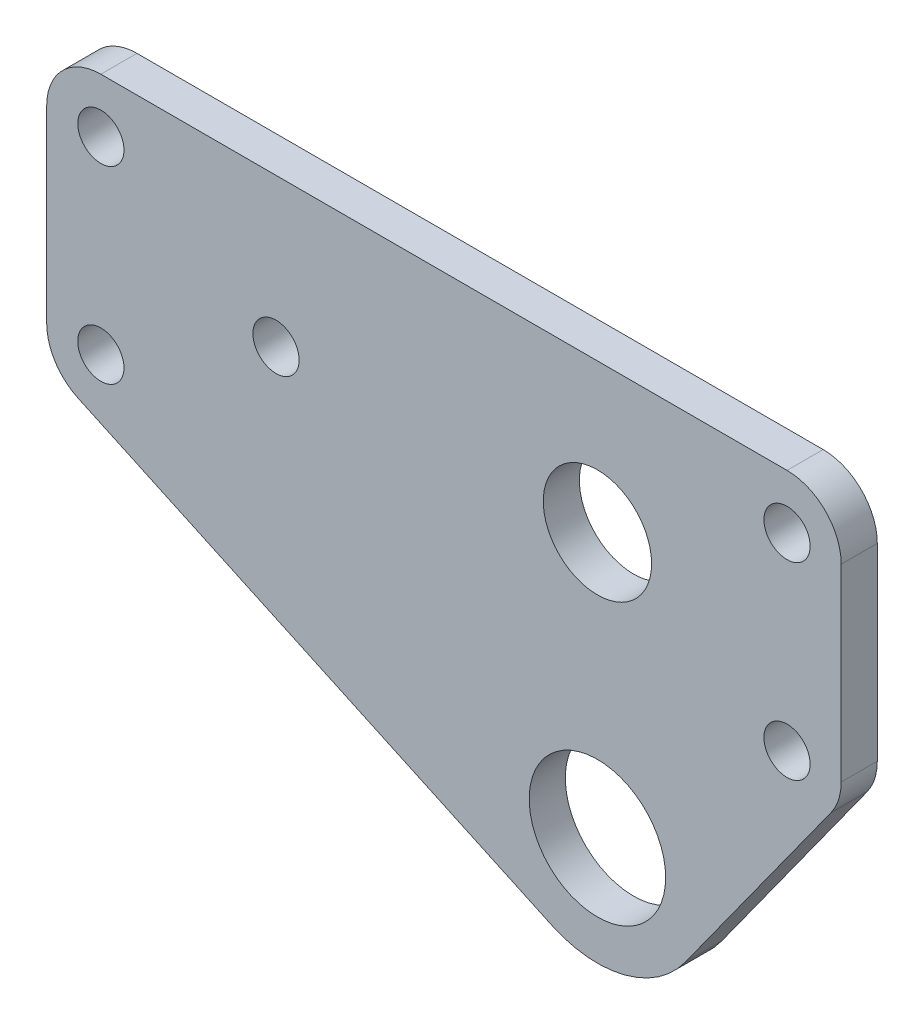
SolidWorks part; units mm, degrees
ref_plane "Front Plane" through (0, 0, 0) normal (0, 0, 1) x (1, 0, 0)
ref_plane "Top Plane" through (0, 0, 0) normal (0, 1, 0) x (1, 0, 0)
ref_plane "Right Plane" through (0, 0, 0) normal (1, 0, 0) x (0, 0, -1)
sketch "Sketch1" plane through (0, 0, 0) normal (0, 0, 1) x (1, 0, 0)
  line L0 (0, 0) -> (26.9875, 0) construction
  line L2 (43.6562, -13.0556) -> (-16.6687, -13.0556)
  line L3 (48.4188, -8.2931) -> (48.4188, 8.2931)
  line L4 (43.6562, 13.0556) -> (-16.6687, 13.0556)
  line L5 (-21.4312, -8.2931) -> (-21.4312, 8.2931)
  line L6 (48.4188, -13.0556) -> (-21.4312, 13.0556) construction
  line L7 (48.4188, 13.0556) -> (-21.4312, -13.0556) construction
  circle A0 centre (0, 0) radius 6 construction
  circle A1 centre (26.9875, 0) radius 4.7625
  arc A2 (48.4188, 8.2931) -> (43.6562, 13.0556) centre (43.6562, 8.2931) ccw
  arc A3 (43.6562, -13.0556) -> (48.4188, -8.2931) centre (43.6562, -8.2931) ccw
  arc A4 (-16.6687, -13.0556) -> (-21.4312, -8.2931) centre (-16.6687, -8.2931) cw
  arc A5 (-16.6687, 13.0556) -> (-21.4312, 8.2931) centre (-16.6687, 8.2931) ccw
  circle A6 centre (0, 0) radius 13.7592 construction
  circle A7 centre (26.9875, 0) radius 15.3467 construction
  circle A8 centre (-16.6687, 8.2931) radius 2.032
  circle A9 centre (43.6562, 8.2931) radius 2.032
  circle A10 centre (-16.6687, -8.2931) radius 2.032
  circle A11 centre (43.6562, -8.2931) radius 2.032
  circle A12 centre (-1.27, 0) radius 2.032
  point P5 (13.4937, 0)
  dimension "D1" = 12
  dimension "D2" = 26.9875
  dimension "D5" = 4.7625
  dimension "D6" = 27.5184
  dimension "D7" = 30.6934
  dimension "D8" = 4.064
  dimension "D9" = 9.525
  dimension "D3" = 26.1112
  dimension "D4" = 69.85
  dimension "D10" = 28.2575
extrude "Boss-Extrude1" add sketch "Sketch1" along normal blind 3.175
sketch "Sketch2" plane through (0, 0, 3.175) normal (0, 0, 1) x (1, 0, 0)
  line L0 (26.9875, 0) -> (26.9875, -23.2833) construction
  line L1 (22.9812, -31.9248) -> (-18.6719, -12.6138)
  line L2 (34.7159, -28.8509) -> (47.5204, -11.0769)
  line L3 (-16.6687, -13.0556) -> (43.6562, -13.0556) construction
  line L4 (-16.6687, -13.0556) -> (43.6562, -13.0556)
  circle A0 centre (26.9875, -23.2833) radius 6
  arc A1 (22.9812, -31.9248) -> (34.7159, -28.8509) centre (26.9875, -23.2833) ccw
  arc A2 (-21.4312, -8.2931) -> (-16.6687, -13.0556) centre (-16.6687, -8.2931) ccw construction
  arc A4 (43.6562, -13.0556) -> (48.4188, -8.2931) centre (43.6562, -8.2931) ccw construction
  arc A5 (-18.6719, -12.6138) -> (-16.6687, -13.0556) centre (-16.6687, -8.2931) ccw
  arc A6 (43.6562, -13.0556) -> (47.5204, -11.0769) centre (43.6562, -8.2931) ccw
  point P6 (45.7069, -12.5915)
  dimension "D1" = 12
  dimension "D3" = 9.525
  dimension "D2" = 23.2833
extrude "Boss-Extrude2" add sketch "Sketch2" against normal up to surface (3.175 mm away) up to face at (13.4938, 0, 0)
